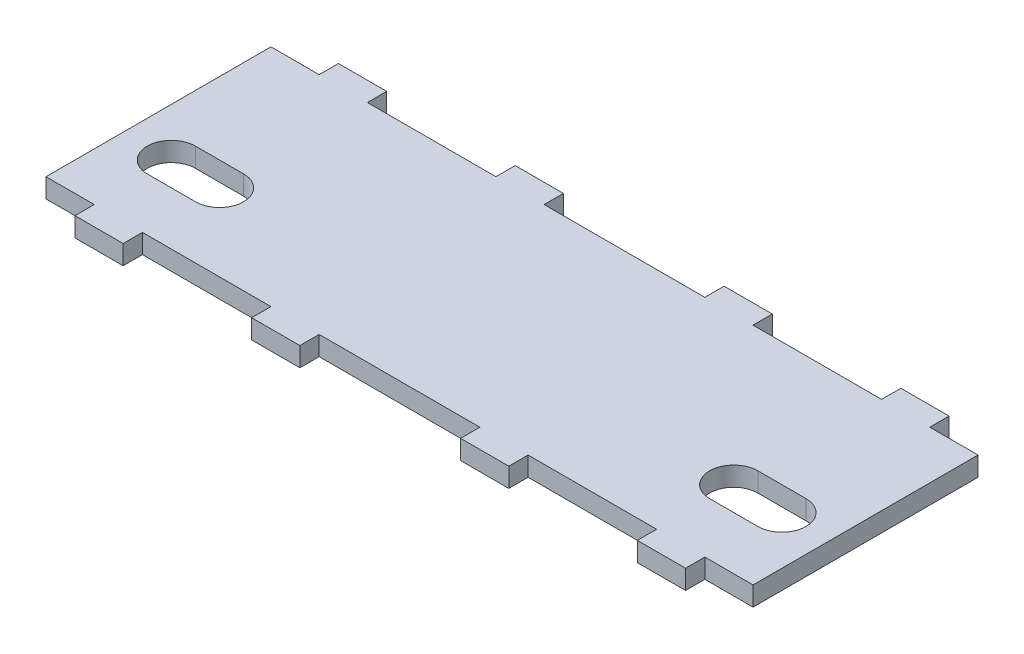
SolidWorks part; units mm, degrees
material "Acrylic (Medium-high impact)"
ref_plane "Front Plane" through (0, 0, 0) normal (0, 0, 1) x (1, 0, 0)
ref_plane "Top Plane" through (0, 0, 0) normal (0, 1, 0) x (1, 0, 0)
ref_plane "Right Plane" through (0, 0, 0) normal (1, 0, 0) x (0, 0, -1)
sketch "Sketch1" plane through (0, 0, 0) normal (0, 1, 0) x (1, 0, 0)
  line L0 (-160.3867, 60.5) -> (-145.3867, 60.5)
  line L1 (-365.3867, 60.5) -> (-350.3867, 60.5)
  line L2 (-365.3867, 60.5) -> (-365.3867, -9.5)
  line L3 (-365.3867, -9.5) -> (-350.3867, -9.5)
  line L4 (-145.3867, 60.5) -> (-145.3867, -9.5)
  line L6 (-350.3867, 60.5) -> (-350.3867, 66.5)
  line L7 (-350.3867, 66.5) -> (-335.3867, 66.5)
  line L8 (-335.3867, 60.5) -> (-335.3867, 66.5)
  line L10 (-295.3867, 60.5) -> (-295.3867, 66.5)
  line L11 (-295.3867, 66.5) -> (-280.3867, 66.5)
  line L12 (-280.3867, 60.5) -> (-280.3867, 66.5)
  line L14 (-175.3867, 60.5) -> (-175.3867, 66.5)
  line L15 (-175.3867, 66.5) -> (-160.3867, 66.5)
  line L16 (-160.3867, 60.5) -> (-160.3867, 66.5)
  line L17 (-280.3867, 60.5) -> (-230.3867, 60.5)
  line L18 (-335.3867, 60.5) -> (-295.3867, 60.5)
  line L19 (-365.3867, -15.5) -> (-350.8867, -15.5) construction
  line L21 (-350.3867, -9.5) -> (-350.3867, -15.5)
  line L22 (-350.3867, -15.5) -> (-335.3867, -15.5)
  line L23 (-335.3867, -9.5) -> (-335.3867, -15.5)
  line L25 (-295.3867, -9.5) -> (-295.3867, -15.5)
  line L26 (-295.3867, -15.5) -> (-280.3867, -15.5)
  line L27 (-280.3867, -9.5) -> (-280.3867, -15.5)
  line L29 (-175.3867, -9.5) -> (-175.3867, -15.5)
  line L30 (-175.3867, -15.5) -> (-160.3867, -15.5)
  line L31 (-160.3867, -9.5) -> (-160.3867, -15.5)
  line L32 (-335.3867, -9.5) -> (-295.3867, -9.5)
  line L33 (-280.3867, -9.5) -> (-230.3867, -9.5)
  line L34 (-160.3867, -9.5) -> (-145.3867, -9.5)
  line L35 (-215.3867, -9.5) -> (-175.3867, -9.5)
  line L37 (-230.3867, -9.5) -> (-230.3867, -15.5)
  line L38 (-230.3867, -15.5) -> (-215.3867, -15.5)
  line L39 (-215.3867, -9.5) -> (-215.3867, -15.5)
  line L40 (-215.3867, 60.5) -> (-175.3867, 60.5)
  line L42 (-230.3867, 60.5) -> (-230.3867, 66.5)
  line L43 (-230.3867, 66.5) -> (-215.3867, 66.5)
  line L44 (-215.3867, 60.5) -> (-215.3867, 66.5)
  point P34 (-255.3867, -9.5)
  dimension "D1" = 70
  dimension "D2" = 220
  dimension "D3" = 6
  dimension "D4" = 6
  dimension "D5" = 6
  dimension "D6" = 15
  dimension "D7" = 15
  dimension "D8" = 15
  dimension "D9" = 15
  dimension "D10" = 15
  dimension "D11" = 15
  dimension "D12" = 6
  dimension "D13" = 6
  dimension "D14" = 6
  dimension "D15" = 15
  dimension "D16" = 50
  dimension "D17" = 110
  dimension "D18" = 0
  dimension "D19" = 6
extrude "Boss-Extrude1" add sketch "Sketch1" along normal blind 6
sketch "Sketch2" plane through (0, 0, 0) normal (0, -1, 0) x (1, 0, 0)
  line L0 (-365.3867, -60.5) -> (-365.3867, 9.5) construction
  line L1 (-365.3867, 15.5) -> (-350.8867, 15.5) construction
  line L2 (-145.3867, 9.5) -> (-145.3867, -60.5) construction
  line L3 (-350.3867, -7) -> (-335.3867, -7)
  line L4 (-350.3867, -22) -> (-335.3867, -22)
  line L5 (-175.3867, -22) -> (-160.3867, -22)
  line L6 (-160.3867, -7) -> (-175.3867, -7)
  arc A0 (-350.3867, -7) -> (-350.3867, -22) centre (-350.3867, -14.5) ccw
  arc A1 (-160.3867, -22) -> (-160.3867, -7) centre (-160.3867, -14.5) ccw
  arc A2 (-335.3867, -22) -> (-335.3867, -7) centre (-335.3867, -14.5) ccw
  arc A3 (-175.3867, -7) -> (-175.3867, -22) centre (-175.3867, -14.5) ccw
  dimension "D3" = 15
  dimension "D4" = 15
  dimension "D6" = 15
  dimension "D7" = 15
  dimension "D1" = 15
  dimension "D2" = 30
  dimension "D5" = 15
  dimension "D8" = 15
  dimension "D9" = 15
extrude "Cut-Extrude1" cut sketch "Sketch2" against normal blind 10
